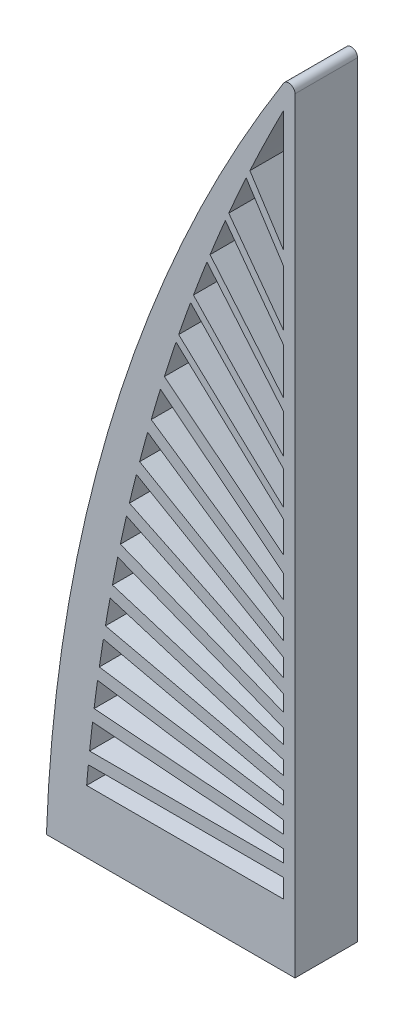
SolidWorks part; units mm, degrees
ref_plane "Front Plane" through (0, 0, 0) normal (0, 0, 1) x (1, 0, 0)
ref_plane "Top Plane" through (0, 0, 0) normal (0, 1, 0) x (1, 0, 0)
ref_plane "Right Plane" through (0, 0, 0) normal (1, 0, 0) x (0, 0, -1)
sketch "Sketch1" plane through (0, 0, 0) normal (0, 1, 0) x (1, 0, 0)
  line L1 (-9.5, 8) -> (9.5, 8) construction
  line L2 (-9.5, 8) -> (-9.5, -8) construction
  line L3 (-9.5, -8) -> (9.5, -8) construction
  line L4 (9.5, 8) -> (9.5, -8) construction
  line L5 (-9.5, 8) -> (9.5, -8) construction
  line L6 (-9.5, -8) -> (9.5, 8) construction
  line L7 (12, 10.5) -> (-12, 10.5)
  line L8 (12, 10.5) -> (12, -10.5)
  line L9 (12, -10.5) -> (-12, -10.5)
  line L10 (-12, 10.5) -> (-12, -10.5)
  line L11 (12, 10.5) -> (-12, -10.5) construction
  line L12 (12, -10.5) -> (-12, 10.5) construction
  circle A0 centre (-9.5, 8) radius 1.625
  circle A1 centre (9.5, 8) radius 1.625
  circle A2 centre (9.5, -8) radius 1.625
  circle A3 centre (-9.5, -8) radius 1.625
  point P0 (0, 0)
  point P10 (0, 0)
  dimension "D3" = 3.25
  dimension "D1" = 24
  dimension "D2" = 21
  dimension "D4" = 19
  dimension "D5" = 16
extrude "Boss-Extrude1" [suppressed] add sketch "Sketch1" along normal blind 7.5
sketch "Sketch5" plane through (0, 0, 0) normal (0, 0, 1) x (1, 0, 0)
  line L0 (0, 0) -> (0, 122.3647)
  line L1 (-39.7203, 0) -> (0, 0)
  line L2 (-1.8, 10) -> (-33.298, 10)
  line L98 (-1.8, 10) -> (-1.8, 119.1977)
  arc A0 (0, 122.3647) -> (-1.8463, 122.8974) centre (-1, 122.3647) ccw
  arc A1 (-1.8463, 122.8974) -> (-39.7203, 0) centre (207.5727, -8.9251) ccw
  arc A8 (-0.0258, 122.5904) -> (-33.298, 10) centre (259.6074, -15.3467) ccw construction
  arc A23 (-1.8, 119.1977) -> (-33.298, 10) centre (259.6074, -15.3467) ccw construction
  arc A42 (-1.8, 119.1977) -> (-33.298, 10) centre (259.6074, -15.3467) ccw
  dimension "D3" = 247.454
  dimension "D4" = 1
  dimension "D1" = 39.7203
  dimension "D2" = 122.3647
  dimension "D5" = 10
  dimension "D6" = 1.8
  dimension "D7" = 109.1977
  dimension "D8" = 31.498
extrude "Boss-Extrude4" add sketch "Sketch5" along normal blind 10
sketch "Sketch8" plane through (0, 0, 0) normal (0, 0, 1) x (1, 0, 0)
  line L52 (-1.8, 13) -> (-33.0229, 13)
  line L55 (-32.8223, 15) -> (-1.8, 15)
  line L99 (-1.8, 13) -> (-1.8, 15)
  line L100 (-33.298, 10) -> (-1.8, 10) construction
  line L101 (-1.8, 10) -> (-1.8, 119.1977) construction
  line L103 (54.8264, 10) -> (0, 10) construction
  line L104 (-1.8, 16.9501) -> (-32.3512, 19.2395)
  line L105 (-32.1089, 21.2269) -> (-1.8, 18.9557)
  line L107 (-1.8, 20.9448) -> (-31.5513, 25.4289)
  line L108 (-31.2672, 27.4086) -> (-1.8, 22.9673)
  line L110 (-1.8, 25.0307) -> (-30.6188, 31.6082)
  line L111 (-30.2921, 33.585) -> (-1.8, 27.0821)
  line L113 (-1.8, 29.2589) -> (-29.5459, 37.817)
  line L114 (-29.1751, 39.7956) -> (-1.8, 31.3518)
  line L116 (-1.8, 33.6871) -> (-28.3208, 44.0953)
  line L117 (-27.9039, 46.0802) -> (-1.8, 35.8356)
  line L119 (-1.8, 38.3837) -> (-26.9277, 50.484)
  line L120 (-26.4619, 52.4795) -> (-1.8, 40.6035)
  line L122 (-1.8, 43.4319) -> (-25.3458, 57.0255)
  line L123 (-24.8276, 59.0357) -> (-1.8, 45.7413)
  line L125 (-1.8, 48.9367) -> (-23.5489, 63.7642)
  line L126 (-22.9742, 65.793) -> (-1.8, 51.3573)
  line L128 (-1.8, 55.0343) -> (-21.5044, 70.7472)
  line L129 (-20.8682, 72.7979) -> (-1.8, 57.5923)
  line L132 (-1.8, 13) -> (-1.8, 15)
  line L133 (-1.6526, 16.939) -> (-1.5032, 18.9334) [skipped]
  line L134 (-1.2113, 20.856) -> (-0.9132, 22.8337) [skipped]
  line L135 (-0.4785, 24.7291) -> (-0.0335, 26.679) [skipped]
  line L136 (0.5417, 28.5366) -> (1.1312, 30.4477) [skipped]
  line L137 (1.8435, 32.2572) -> (2.5742, 34.1189) [skipped]
  line L138 (5.2616, 39.3551) -> (6.2615, 41.0872) [skipped]
  line L139 (3.4197, 35.8701) -> (4.2875, 37.672) [skipped]
  line L140 (7.3586, 42.6928) -> (8.4852, 44.3453) [skipped]
  line L141 (9.6993, 45.8644) -> (10.9462, 47.4281) [skipped]
  line L142 (-1.8, 55.0343) -> (-1.8, 57.5923)
  line L143 (-1.8, 48.9367) -> (-1.8, 51.3573)
  line L144 (-1.8, 16.9501) -> (-1.8, 18.9557)
  line L145 (-1.8, 20.9448) -> (-1.8, 22.9673)
  line L146 (-1.8, 25.0307) -> (-1.8, 27.0821)
  line L147 (-1.8, 38.3837) -> (-1.8, 40.6035)
  line L148 (-1.8, 29.2589) -> (-1.8, 31.3518)
  line L149 (-1.8, 33.6871) -> (-1.8, 35.8356)
  line L150 (-1.8, 62.5395) -> (-19.0097, 78.5071)
  line L152 (-18.5872, 79.7521) -> (-1.8, 64.1765)
  line L153 (-1.8, 62.5395) -> (54.8264, 10) construction
  line L154 (-1.8, 69.5027) -> (-16.6853, 85.1441)
  line L155 (-16.2249, 86.401) -> (-1.8, 71.2434)
  line L156 (-1.8, 77.4408) -> (-14.0722, 92.0568)
  line L157 (-13.5708, 93.3258) -> (-1.8, 79.307)
  line L158 (-1.8, 86.6505) -> (-11.1277, 99.2767)
  line L159 (-10.5819, 100.5574) -> (-1.8, 88.6701)
  line L160 (-1.8, 97.5556) -> (-7.8016, 106.8353)
  line L161 (-7.2078, 108.1267) -> (-1.8, 99.7652)
  line L162 (54.8264, 10) -> (-1.8, 62.5395) construction
  line L163 (-1.8, 13) -> (-1.8, 15)
  line L164 (-1.8, 97.5556) -> (-1.8, 99.7652)
  line L165 (-1.8, 86.6505) -> (-1.8, 88.6701)
  line L166 (-1.8, 77.4408) -> (-1.8, 79.307)
  line L167 (-1.8, 69.5027) -> (-1.8, 71.2434)
  line L168 (-1.8, 62.5395) -> (-1.8, 64.1765)
  line L169 (-1.8, 55.0343) -> (-1.8, 57.5923)
  line L170 (-1.8, 48.9367) -> (-1.8, 51.3573)
  line L171 (-1.8, 16.9501) -> (-1.8, 22.9673)
  line L172 (-1.8, 25.0307) -> (-1.8, 27.0821)
  line L173 (-1.8, 29.2589) -> (-1.8, 31.3518)
  line L174 (-1.8, 33.6871) -> (-1.8, 35.8356)
  line L175 (-1.8, 38.3837) -> (-1.8, 40.6035)
  line L176 (-1.8, 43.4319) -> (-1.8, 45.7413)
  line L177 (-1.8, 43.4319) -> (-1.8, 45.7413)
  line L178 (0, 0) -> (0, 122.3647) construction
  arc A43 (-1.8, 119.1977) -> (-33.298, 10) centre (259.6074, -15.3467) ccw construction
  arc A54 (-20.8682, 72.7979) -> (-21.5044, 70.7472) centre (259.6074, -15.3467) ccw
  arc A55 (-22.9742, 65.793) -> (-23.5489, 63.7642) centre (259.6074, -15.3467) ccw
  arc A56 (-24.8276, 59.0357) -> (-25.3458, 57.0255) centre (259.6074, -15.3467) ccw
  arc A57 (-27.9039, 46.0802) -> (-28.3208, 44.0953) centre (259.6074, -15.3467) ccw
  arc A58 (-29.1751, 39.7956) -> (-29.5459, 37.817) centre (259.6074, -15.3467) ccw
  arc A59 (-30.2921, 33.585) -> (-30.6188, 31.6082) centre (259.6074, -15.3467) ccw
  arc A60 (-31.2672, 27.4086) -> (-31.5513, 25.4289) centre (259.6074, -15.3467) ccw
  arc A61 (-32.1089, 21.2269) -> (-32.3512, 19.2395) centre (259.6074, -15.3467) ccw
  arc A62 (-32.8223, 15) -> (-33.0229, 13) centre (259.6074, -15.3467) ccw
  arc A63 (-7.2078, 108.1267) -> (-7.8016, 106.8353) centre (259.6074, -15.3467) ccw
  arc A64 (-10.5819, 100.5574) -> (-11.1277, 99.2767) centre (259.6074, -15.3467) ccw
  arc A65 (-13.5708, 93.3258) -> (-14.0722, 92.0568) centre (259.6074, -15.3467) ccw
  arc A66 (-16.2249, 86.401) -> (-16.6853, 85.1441) centre (259.6074, -15.3467) ccw
  arc A67 (-18.5872, 79.7521) -> (-19.0097, 78.5071) centre (259.6074, -15.3467) ccw
  arc A68 (-20.8682, 72.7979) -> (-21.5044, 70.7472) centre (259.6074, -15.3467) ccw
  arc A69 (-22.9742, 65.793) -> (-23.5489, 63.7642) centre (259.6074, -15.3467) ccw
  arc A70 (-24.8276, 59.0357) -> (-25.3458, 57.0255) centre (259.6074, -15.3467) ccw
  arc A71 (-32.8223, 15) -> (-33.0229, 13) centre (259.6074, -15.3467) ccw
  arc A72 (-32.1089, 21.2269) -> (-32.3512, 19.2395) centre (259.6074, -15.3467) ccw
  arc A73 (-31.2672, 27.4086) -> (-31.5513, 25.4289) centre (259.6074, -15.3467) ccw
  arc A74 (-30.2921, 33.585) -> (-30.6188, 31.6082) centre (259.6074, -15.3467) ccw
  arc A75 (-29.1751, 39.7956) -> (-29.5459, 37.817) centre (259.6074, -15.3467) ccw
  arc A76 (-27.9039, 46.0802) -> (-28.3208, 44.0953) centre (259.6074, -15.3467) ccw
  arc A77 (-26.4619, 52.4795) -> (-26.9277, 50.484) centre (259.6074, -15.3467) ccw
  arc A78 (-26.4619, 52.4795) -> (-26.9277, 50.484) centre (259.6074, -15.3467) ccw
  point P0 (0, 0)
  dimension "D3" = 42.856
  dimension "D4" = 10
  dimension "D9" = 5.3262
  dimension "D10" = 1.9501
  dimension "D1" = 3
  dimension "D2" = 2
  dimension "D5" = 4.286
  dimension "D6" = 1.2
  dimension "D7" = 77.246
  dimension "D8" = 5
  dimension "D11" = 1.9891
extrude "Boss-Extrude5" add sketch "Sketch8" along normal blind 10 contours L55 A62 L52 L99 | L105 A61 L104 L132 | L108 A60 L107 L132 | L111 A59 L110 L132 | L114 A58 L113 L132 | L117 A57 L116 L132 | L120 A56 L119 L132 | L123 A56 L122 L132 | L126 A55 L125 L132 | L129 A54 L128 L132 | L152 A67 L150 L168 | L155 A66 L154 L167 | L157 A65 L156 L166 | L159 A64 L158 L165 | L161 A63 L160 L164
